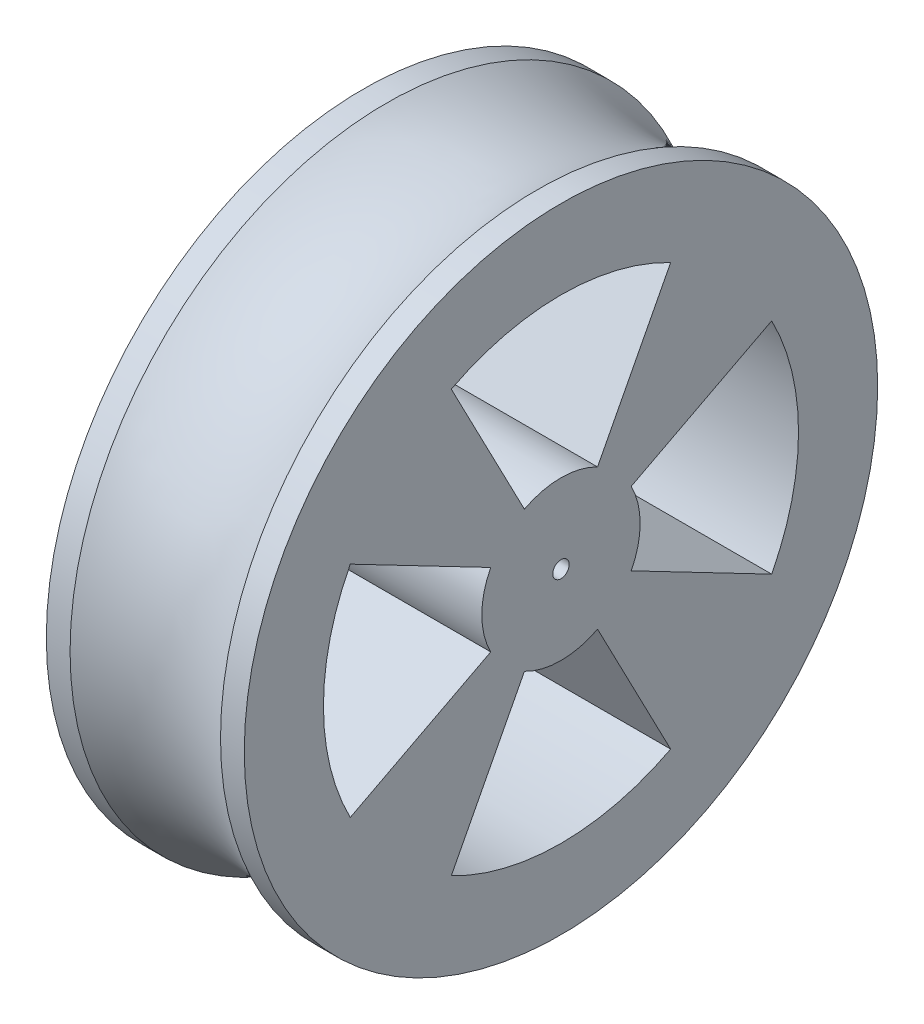
SolidWorks part; units mm, degrees
ref_plane "Front" through (0, 0, 0) normal (0, 0, 1) x (1, 0, 0)
ref_plane "Top" through (0, 0, 0) normal (0, 1, 0) x (1, 0, 0)
ref_plane "Right" through (0, 0, 0) normal (1, 0, 0) x (0, 0, -1)
sketch "Sketch1" plane through (0, 0, 0) normal (0, 1, 0) x (1, 0, 0)
  line L0 (-12.5, 0) -> (12.5, 0)
  line L1 (-12.5, 0) -> (-12.5, 40)
  line L3 (12.5, 40) -> (12.5, 0)
  line L4 (-12.5, 40) -> (-9.5, 40)
  line L5 (12.5, 40) -> (9.5, 40)
  arc A1 (-9.5, 40) -> (9.5, 40) centre (0, 57.5997) ccw
  point P4 (0, 0)
  dimension "D3" = 3
  dimension "D5" = 20
  dimension "D1" = 25
  dimension "D2" = 40
  dimension "D4" = 3
revolve "Revolve1" add sketch "Sketch1" angle 360 about L0
sketch "Sketch2" plane through (12.5, 0, 0) normal (1, 0, 0) x (0, 0, -1)
  line L0 (-4.6175, 8.8701) -> (-13.8525, 26.6103)
  line L1 (13.8525, 26.6103) -> (4.6175, 8.8701)
  line L2 (-9.235, 17.7402) -> (9.235, 17.7402) construction
  line L3 (26.6103, -13.8525) -> (8.8701, -4.6175)
  line L4 (8.8701, 4.6175) -> (26.6103, 13.8525)
  line L5 (-13.8525, -26.6103) -> (-4.6175, -8.8701)
  line L6 (4.6175, -8.8701) -> (13.8525, -26.6103)
  line L7 (-26.6103, 13.8525) -> (-8.8701, 4.6175)
  line L8 (-8.8701, -4.6175) -> (-26.6103, -13.8525)
  arc A0 (8.8701, -4.6175) -> (8.8701, 4.6175) centre (0, 0) ccw
  arc A1 (13.8525, 26.6103) -> (-13.8525, 26.6103) centre (0, 0) ccw
  arc A2 (26.6103, -13.8525) -> (26.6103, 13.8525) centre (0, 0) ccw
  arc A3 (4.6175, 8.8701) -> (-4.6175, 8.8701) centre (0, 0) ccw
  arc A4 (-8.8701, 4.6175) -> (-8.8701, -4.6175) centre (0, 0) ccw
  arc A5 (-26.6103, 13.8525) -> (-26.6103, -13.8525) centre (0, 0) ccw
  arc A6 (-13.8525, -26.6103) -> (13.8525, -26.6103) centre (0, 0) ccw
  arc A7 (-4.6175, -8.8701) -> (4.6175, -8.8701) centre (0, 0) ccw
  point P10 (0, 17.7402)
  dimension "D1" = 20
  dimension "D2" = 60
  dimension "D3" = 55
  dimension "D4" = 4
extrude "Cut-Extrude1" cut sketch "Sketch2" against normal through all
hole_wizard "Ø2.05 (2.08) Diameter Hole1" positions "Sketch3" profile "Sketch4" hole size "Ø2.05" standard "ANSI Metric"
sketch "Sketch3" plane through (12.5, 0, 0) normal (1, 0, 0) x (0, 0, -1)
  point P0 (0, 0)
sketch "Sketch4" plane through (12.5, 0, 0) normal (0, 1, 0) x (0, 0, -1)
  line L0 (0, 0) -> (0, 20.6249)
  line L1 (0, 20.6249) -> (1.04, 20)
  line L2 (1.04, 20) -> (1.04, 0)
  line L5 (1.04, 0) -> (0, 0)
  line L10 (0, 20.6249) -> (-1.04, 20) construction
  line L11 (0, -6.35) -> (0, 107.95) construction
  dimension "Hole Dia." = 2.08
  dimension "Hole Depth" = 20
  dimension "Drill Angle" = 118
